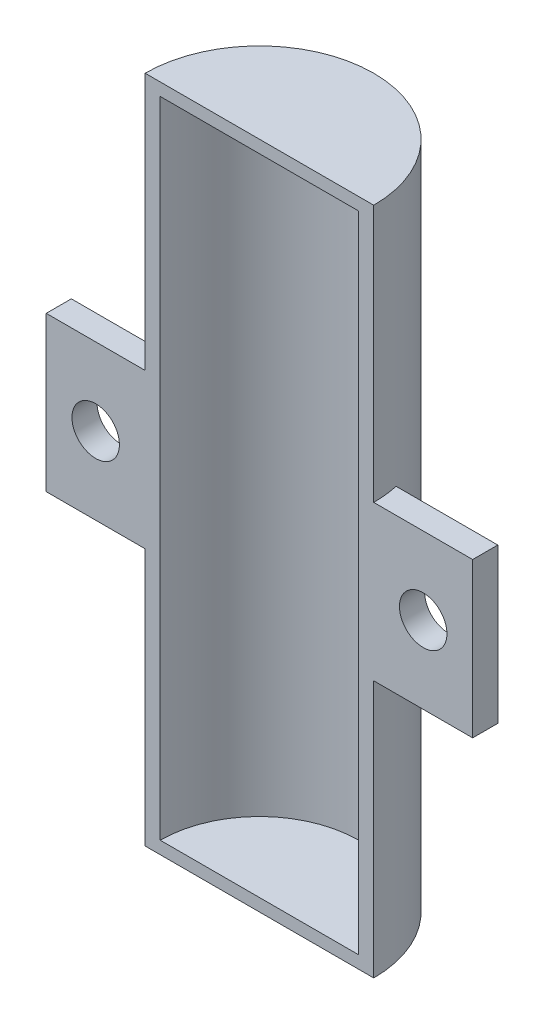
SolidWorks part; units mm, degrees
material "ABS"
ref_plane "X-Y Datum" through (0, 0, 0) normal (0, 0, 1) x (1, 0, 0)
ref_plane "X-Z Datum" through (0, 0, 0) normal (0, 1, 0) x (1, 0, 0)
ref_plane "Y-Z Datum" through (0, 0, 0) normal (1, 0, 0) x (0, 0, -1)
sketch "Sketch1" plane through (0, 0, 0) normal (0, 1, 0) x (1, 0, 0)
  line L0 (-11.557, 0) -> (-10.033, 0)
  line L1 (10.033, 0) -> (11.557, 0)
  arc A0 (10.033, 0) -> (-10.033, 0) centre (0, 0) ccw
  arc A1 (11.557, 0) -> (-11.557, 0) centre (0, 0) ccw
  circle A2 centre (0, 0) radius 11.557 construction
  circle A3 centre (0, 0) radius 10.033 construction
  dimension "D1" = 1.524
extrude "Boss-Extrude1" add sketch "Sketch1" along normal blind 66.3956
sketch "Sketch2" plane through (0, 66.3956, 0) normal (0, 1, 0) x (1, 0, 0)
  line L0 (-11.557, 0) -> (11.557, 0)
  arc A0 (11.557, 0) -> (-11.557, 0) centre (0, 0) ccw
extrude "Boss-Extrude2" add sketch "Sketch2" along normal blind 1.27
sketch "Sketch3" [suppressed] plane through (0, 67.6656, 0) normal (0, 1, 0) x (1, 0, 0)
  line L0 (-11.557, 0) -> (11.557, 0)
  line L8 (-11.8816, 2.0955) -> (11.8816, 2.0955)
  line L9 (-12.0543, -0.508) -> (12.0543, -0.508) construction
  line L10 (-11.557, 0) -> (-12.065, 0)
  line L11 (11.557, 0) -> (12.065, 0)
  line L14 (-11.4474, 1.5875) -> (11.4474, 1.5875) construction
  arc A1 (11.557, 0) -> (-11.557, 0) centre (0, 0) ccw construction
  arc A2 (11.4495, 1.5727) -> (11.4474, 1.5875) centre (0, 0) ccw
  arc A3 (12.065, 0) -> (11.8816, 2.0955) centre (0, 0) ccw
  arc A4 (-12.065, 0) -> (-11.8816, 2.0955) centre (0, 0) cw
  arc A5 (-12.0543, -0.508) -> (-11.8816, 2.0955) centre (0, 0) cw construction
  arc A6 (12.0543, -0.508) -> (11.8816, 2.0955) centre (0, 0) ccw construction
  arc A7 (11.557, 0) -> (11.4474, 1.5875) centre (0, 0) ccw construction
  arc A8 (-11.557, 0) -> (-11.4474, 1.5875) centre (0, 0) cw construction
  point P0 (0, 0)
  arc M3 (11.557, 0) -> (-11.557, 0) centre (0, 0) ccw
  line M4 (-11.557, 0) -> (11.557, 0)
  dimension "D1" = 0.508
extrude "Boss-Extrude3" [suppressed] add sketch "Sketch3" along normal blind 23.2664 contours L8 M3 M4
sketch "Sketch5" [suppressed] plane through (0, 0, -2.0955) normal (0, 0, -1) x (-1, 0, 0)
  line L0 (-4.572, 83.4026) -> (-4.572, 74.9689)
  line L1 (4.572, 83.4026) -> (4.572, 74.9689)
  arc A0 (4.572, 83.4026) -> (-4.572, 83.4026) centre (0, 83.4026) ccw
  arc A1 (-4.572, 74.9689) -> (4.572, 74.9689) centre (0, 74.9689) ccw
extrude "Cut-Extrude1" [suppressed] cut sketch "Sketch5" against normal through all
ref_plane "Plane1" [suppressed] through (0, 33.8328, 0) normal (0, 1, 0) x (1, 0, 0)
mirror "Mirror1" about plane through (0, 33.8328, 0) normal (0, 1, 0) of "Boss-Extrude2", "Boss-Extrude3", "Cut-Extrude1"
sketch "Sketch6" plane through (0, 0, 0) normal (0, 0, 1) x (1, 0, 0)
  line L0 (-11.557, 67.6656) -> (-11.557, 0) construction
  line L1 (-11.557, 26.0237) -> (-21.557, 26.0237)
  line L3 (-11.557, 41.6419) -> (-21.557, 41.6419)
  line L4 (-21.557, 26.0237) -> (-21.557, 41.6419)
  line L5 (-11.557, 33.8328) -> (-21.557, 41.6419) construction
  line L6 (-11.557, 33.8328) -> (-21.557, 26.0237) construction
  line L7 (-11.557, 41.6419) -> (-11.557, 26.0237)
  line L8 (-21.557, 33.8328) -> (-11.557, 33.8328) construction
  line L9 (-16.557, 41.6419) -> (-16.557, 33.8328) construction
  line L10 (-11.557, 41.6419) -> (-10.033, 41.6419)
  line L11 (-10.033, 66.3956) -> (-10.033, 1.27) construction
  line L12 (-10.033, 41.6419) -> (-10.033, 26.0237)
  line L13 (-10.033, 26.0237) -> (-11.557, 26.0237)
  line L14 (0, 67.6656) -> (0, -1.2384) construction
  line L15 (-11.557, 67.6656) -> (11.557, 67.6656) construction
  line L16 (16.557, 41.6419) -> (16.557, 33.8328) construction
  line L17 (21.557, 33.8328) -> (11.557, 33.8328) construction
  line L18 (11.557, 33.8328) -> (21.557, 26.0237) construction
  line L19 (11.557, 33.8328) -> (21.557, 41.6419) construction
  line L20 (10.033, 26.0237) -> (11.557, 26.0237)
  line L21 (10.033, 41.6419) -> (10.033, 26.0237)
  line L22 (11.557, 41.6419) -> (10.033, 41.6419)
  line L23 (11.557, 41.6419) -> (11.557, 26.0237)
  line L24 (21.557, 26.0237) -> (21.557, 41.6419)
  line L25 (11.557, 41.6419) -> (21.557, 41.6419)
  line L26 (11.557, 26.0237) -> (21.557, 26.0237)
  circle A0 centre (-16.557, 33.8328) radius 0.5921
  circle A1 centre (16.557, 33.8328) radius 0.5921
  point P0 (-11.557, 33.8328)
  point P32 (11.557, 33.8328)
  line M5 (-10.033, 1.27) -> (-10.033, 66.3956)
  line M7 (10.033, 66.3956) -> (10.033, 1.27)
  line M8 (-11.557, 67.6656) -> (-11.557, 0)
  line M10 (11.557, 0) -> (11.557, 67.6656)
extrude "Boss-Extrude4" add sketch "Sketch6" against normal blind 2.54 contours L4 L1 L3 A0 M8 | L13 L10 M5 M8 | L22 L20 M10 M7 | L26 L24 L25 A1 M10
hole_wizard "M4 Clearance Hole1" positions "Sketch7" profile "Sketch8" hole size "M4" standard "ANSI Metric" end condition through all
sketch "Sketch7" plane through (0, 0, -2.54) normal (0, 0, -1) x (-1, 0, 0)
  point P4 (-16.557, 33.8328)
  point P7 (16.557, 33.8328)
sketch "Sketch8" plane through (16.557, 33.8328, -2.54) normal (1, 0, 0) x (0, 1, 0)
  line L0 (0, 0) -> (0, 2.54)
  line L1 (0, 2.54) -> (2.4, 2.54)
  line L2 (2.4, 2.54) -> (2.4, 0)
  line L5 (2.4, 0) -> (0, 0)
  line L11 (0, -6.35) -> (0, 107.95) construction
  dimension "Thru Hole Dia." = 4.8
  dimension "Thru Hole Depth" = 2.54
